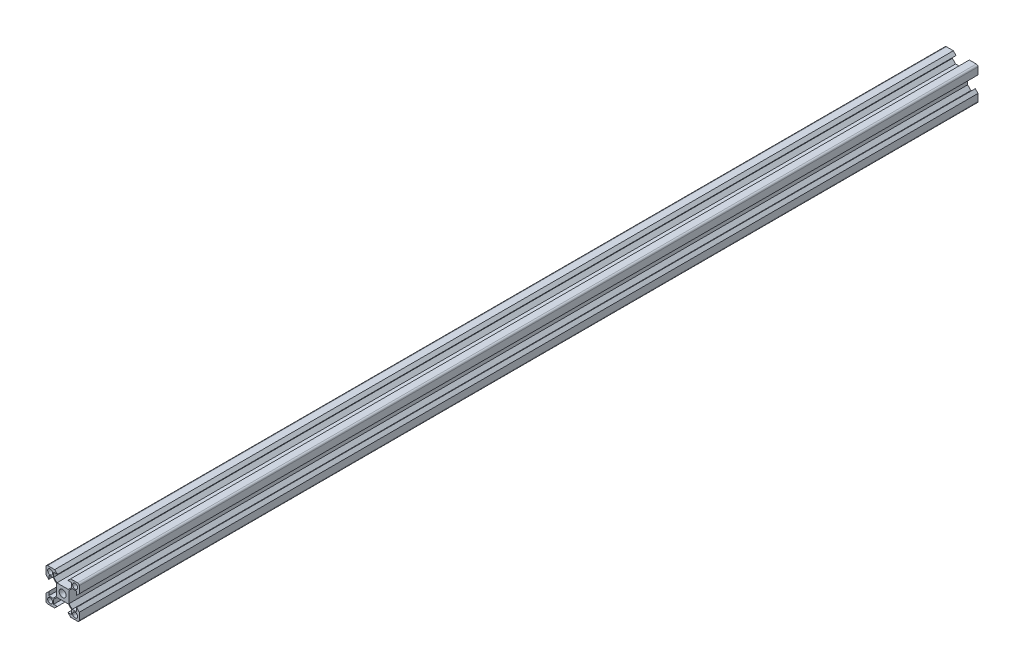
SolidWorks part; units mm, degrees
material "铝管"
ref_plane "前视基准面" through (0, 0, 0) normal (0, 0, 1) x (1, 0, 0)
ref_plane "上视基准面" through (0, 0, 0) normal (0, 1, 0) x (1, 0, 0)
ref_plane "右视基准面" through (0, 0, 0) normal (1, 0, 0) x (0, 0, -1)
sketch "草图1" plane through (0, 0, 0) normal (0, 0, 1) x (1, 0, 0)
  line L0 (0, 0) -> (-40.5659, 40.5659) construction
  line L1 (0, 0) -> (0, 75.5033) construction
  line L2 (-10, 10) -> (-10, 4.8)
  line L3 (-10, 4.8) -> (-8.34, 3.14)
  line L4 (-8.34, 3.14) -> (-8.34, 5.4)
  line L5 (-5.7536, 5.4) -> (-3.8, 3.4464)
  line L6 (-3.8, 3.4464) -> (-3.8, -3.4464)
  line L7 (-3.8, 0) -> (15.6715, 0) construction
  line L8 (-5.4, 8.34) -> (-5.4, 5.7536)
  line L9 (-3.4464, 3.8) -> (3.4464, 3.8)
  line L10 (-5.4, 5.7536) -> (-3.4464, 3.8)
  line L11 (-3.14, 8.34) -> (-5.4, 8.34)
  line L12 (-8.34, 5.4) -> (-5.7536, 5.4)
  line L13 (-4.8, 10) -> (-3.14, 8.34)
  line L14 (-10, 10) -> (-4.8, 10)
  line L15 (-10, -10) -> (-4.8, -10)
  line L16 (-4.8, -10) -> (-3.14, -8.34)
  line L17 (-8.34, -5.4) -> (-5.7536, -5.4)
  line L18 (-3.14, -8.34) -> (-5.4, -8.34)
  line L19 (-5.4, -5.7536) -> (-3.4464, -3.8)
  line L20 (-3.4464, -3.8) -> (3.4464, -3.8)
  line L21 (-5.4, -8.34) -> (-5.4, -5.7536)
  line L22 (-5.7536, -5.4) -> (-3.8, -3.4464)
  line L23 (-8.34, -3.14) -> (-8.34, -5.4)
  line L24 (-10, -4.8) -> (-8.34, -3.14)
  line L25 (-10, -10) -> (-10, -4.8)
  line L26 (10, -10) -> (10, -4.8)
  line L27 (10, -4.8) -> (8.34, -3.14)
  line L28 (8.34, -3.14) -> (8.34, -5.4)
  line L29 (5.7536, -5.4) -> (3.8, -3.4464)
  line L30 (5.4, -8.34) -> (5.4, -5.7536)
  line L31 (5.4, -5.7536) -> (3.4464, -3.8)
  line L32 (3.14, -8.34) -> (5.4, -8.34)
  line L33 (8.34, -5.4) -> (5.7536, -5.4)
  line L34 (4.8, -10) -> (3.14, -8.34)
  line L35 (10, -10) -> (4.8, -10)
  line L36 (10, 10) -> (4.8, 10)
  line L37 (4.8, 10) -> (3.14, 8.34)
  line L38 (8.34, 5.4) -> (5.7536, 5.4)
  line L39 (3.14, 8.34) -> (5.4, 8.34)
  line L40 (5.4, 5.7536) -> (3.4464, 3.8)
  line L41 (5.4, 8.34) -> (5.4, 5.7536)
  line L42 (3.8, 3.4464) -> (3.8, -3.4464)
  line L43 (5.7536, 5.4) -> (3.8, 3.4464)
  line L44 (8.34, 3.14) -> (8.34, 5.4)
  line L45 (10, 4.8) -> (8.34, 3.14)
  line L46 (10, 10) -> (10, 4.8)
  circle A0 centre (-7.5, 7.5) radius 1.5
  circle A1 centre (0, 0) radius 2.1
  circle A2 centre (-7.5, -7.5) radius 1.5
  circle A3 centre (7.5, -7.5) radius 1.5
  circle A4 centre (7.5, 7.5) radius 1.5
  point P54 (0, -3.8)
  point P64 (0, 3.8)
  dimension "D6" = 3
  dimension "D7" = 7.5
  dimension "D9" = 4.2
  dimension "D1" = 45
  dimension "D2" = 4.8
  dimension "D3" = 3.8
  dimension "D4" = 10
  dimension "D5" = 5.4
  dimension "D8" = 3.14
  dimension "D10" = 10
  dimension "D11" = 0.5
extrude "凸台-拉伸1" add sketch "草图1" along normal mid plane 540
fillet "圆角1" radius 1 4 edges at (-10, -10, 0) (10, -10, 0) (-10, 10, 0) (10, 10, 0)
